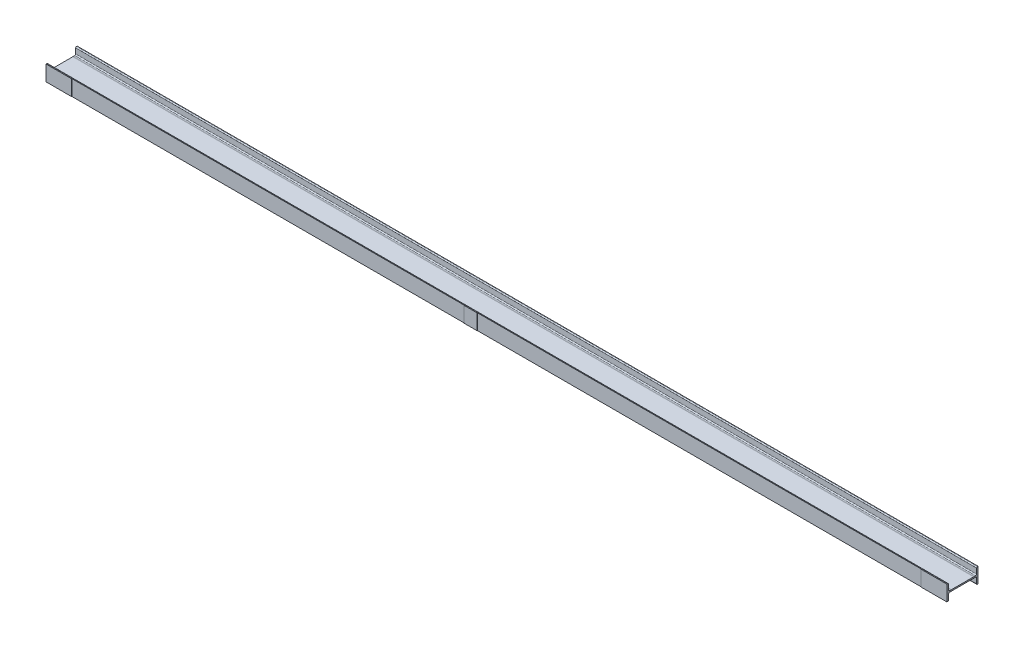
SolidWorks part; units mm, degrees
material "Hierro dúctil"
ref_plane "Alzado" through (0, 0, 0) normal (0, 0, 1) x (1, 0, 0)
ref_plane "Planta" through (0, 0, 0) normal (0, 1, 0) x (1, 0, 0)
ref_plane "Vista lateral" through (0, 0, 0) normal (1, 0, 0) x (0, 0, -1)
sketch "Croquis1" plane through (0, 0, 0) normal (0, 0, 1) x (1, 0, 0)
  line L0 (0, 0) -> (3500, 0)
  dimension "D1" = 3500
other "Viga sb 120 X 12(2)"
ref_plane "Plano1" through (0, 0, 0) normal (1, 0, 0) x (0, 1, 0)
sketch "Sketch12" plane through (0, 0, 0) normal (1, 0, 0) x (0, 1, 0)
  line L0 (-30, -60) -> (-30, -58.0801)
  line L1 (-26.6576, -54.1345) -> (-9.1847, -51.2221)
  line L2 (-2.5, -43.331) -> (-2.5, 43.331)
  line L3 (-9.1847, 51.2221) -> (-26.6576, 54.1345)
  line L4 (-30, 58.0801) -> (-30, 60)
  line L5 (-30, 60) -> (30, 60)
  line L6 (30, 60) -> (30, 58.0801)
  line L7 (26.6576, 54.1345) -> (9.1847, 51.2221)
  line L8 (2.5, 43.331) -> (2.5, -43.331)
  line L9 (9.1847, -51.2221) -> (26.6576, -54.1345)
  line L10 (30, -58.0801) -> (30, -60)
  line L11 (30, -60) -> (-30, -60)
  line L15 (-2.5, 0) -> (2.5, 0) construction
  arc A0 (-9.1847, -51.2221) -> (-2.5, -43.331) centre (-10.5, -43.331) ccw
  arc A1 (-2.5, 43.331) -> (-9.1847, 51.2221) centre (-10.5, 43.331) ccw
  arc A2 (9.1847, 51.2221) -> (2.5, 43.331) centre (10.5, 43.331) ccw
  arc A3 (2.5, -43.331) -> (9.1847, -51.2221) centre (10.5, -43.331) ccw
  arc A4 (-26.6576, 54.1345) -> (-30, 58.0801) centre (-26, 58.0801) cw
  arc A5 (26.6576, 54.1345) -> (30, 58.0801) centre (26, 58.0801) ccw
  arc A6 (-30, -58.0801) -> (-26.6576, -54.1345) centre (-26, -58.0801) cw
  arc A7 (30, -58.0801) -> (26.6576, -54.1345) centre (26, -58.0801) ccw
  point P1 (0, 60)
  point P8 (0, -60)
  point P21 (0, 0)
  point P34 (0, 0)
  dimension "RI" = 8
  dimension "D3" = 4
  dimension "BF" = 60
  dimension "D2" = 9.463
  dimension "DEPTH" = 120
  dimension "TW" = 5
  dimension "D1" = 86.662
sketch "Croquis3" plane through (0, 0, 0) normal (-1, 0, 0) x (0, 0, 1)
  line L0 (0, 0) -> (0, 20.5092) construction
  line L1 (54.1345, 26.6576) -> (44.9002, 26.6576)
  line L2 (54.1345, 26.6576) -> (54.1345, 6.6554)
  line L3 (50.1345, 2.6554) -> (44.9002, 2.6554)
  line L4 (44.9002, 26.6576) -> (44.9002, 2.6554)
  line L5 (54.1345, -26.6576) -> (43.331, -26.6576)
  line L6 (54.1345, -26.6576) -> (54.1345, -6.5)
  line L7 (50.1345, -2.5) -> (43.331, -2.5)
  line L8 (43.331, -26.6576) -> (43.331, -2.5)
  line L9 (-43.331, -26.6576) -> (-43.331, -2.5)
  line L10 (-50.1345, -2.5) -> (-43.331, -2.5)
  line L11 (-54.1345, -26.6576) -> (-54.1345, -6.5)
  line L12 (-54.1345, -26.6576) -> (-43.331, -26.6576)
  line L13 (-44.9002, 26.6576) -> (-44.9002, 2.6554)
  line L14 (-50.1345, 2.6554) -> (-44.9002, 2.6554)
  line L15 (-54.1345, 26.6576) -> (-54.1345, 6.6554)
  line L16 (-54.1345, 26.6576) -> (-44.9002, 26.6576)
  arc A1 (43.331, 2.5) -> (51.2221, 9.1847) centre (43.331, 10.5) ccw construction
  arc A2 (54.1345, -6.5) -> (50.1345, -2.5) centre (50.1345, -6.5) ccw
  arc A3 (50.1345, 2.6554) -> (54.1345, 6.6554) centre (50.1345, 6.6554) ccw
  arc A4 (-54.1345, -6.5) -> (-50.1345, -2.5) centre (-50.1345, -6.5) cw
  arc A5 (-50.1345, 2.6554) -> (-54.1345, 6.6554) centre (-50.1345, 6.6554) cw
  point P30 (54.1345, -2.5)
  point P33 (54.1345, 2.6554)
  point P36 (-54.1345, -2.5)
  point P39 (-54.1345, 2.6554)
  dimension "D5" = 4
  dimension "D1" = 24.0022
  dimension "D2" = 9.2343
  dimension "D3" = 24.1576
  dimension "D4" = 10.8035
extrude "Cortar-Extruir1" cut sketch "Croquis3" against normal through all both and the other way through all
sketch "Croquis4" plane through (0, 0, 60) normal (0, 0, 1) x (1, 0, 0)
  line L0 (3500, 30) -> (0, 30) construction
  line L1 (1624.8292, -30) -> (1675.1708, -30)
  line L2 (1624.8292, -30) -> (1624.8292, 30)
  line L3 (1624.8292, 30) -> (1675.1708, 30)
  line L4 (1675.1708, -30) -> (1675.1708, 30)
  line L5 (1624.8292, -30) -> (1675.1708, 30) construction
  line L6 (1624.8292, 30) -> (1675.1708, -30) construction
  point P0 (1650, 0)
  dimension "D1" = 60
  dimension "D2" = 50.3417
  dimension "D3" = 1650
extrude "Saliente-Extruir1" add sketch "Croquis4" along normal blind 1 separate body
sketch "Croquis6" plane through (0, 0, 60) normal (0, 0, 1) x (1, 0, 0)
  line L2 (3500, 30) -> (3400, 30)
  line L3 (3500, 30) -> (3500, -30)
  line L4 (3500, -30) -> (3400, -30)
  line L5 (3500, -30) -> (0, -30) construction
  line L7 (3400, 30) -> (3400, -30)
  line L8 (0, 30) -> (100, 30)
  line L9 (0, 30) -> (0, -30)
  line L10 (0, -30) -> (100, -30)
  line L12 (100, 30) -> (100, -30)
  dimension "D1" = 60
  dimension "D2" = 60
  dimension "D3" = 100
  dimension "D4" = 100
extrude "Saliente-Extruir2" add sketch "Croquis6" along normal blind 1 separate body
sketch "Croquis7" plane through (0, 0, 0) normal (-1, 0, 0) x (0, 0, 1)
  line L1 (54.1345, -6.6554) -> (-54.1345, -6.6554)
  line L2 (54.1345, -6.6554) -> (54.1345, 6.6554)
  line L3 (54.1345, 6.6554) -> (-54.1345, 6.6554)
  line L4 (-54.1345, -6.6554) -> (-54.1345, 6.6554)
  line L5 (54.1345, -6.6554) -> (-54.1345, 6.6554) construction
  line L6 (54.1345, 6.6554) -> (-54.1345, -6.6554) construction
  point P0 (0, 0)
  dimension "D1" = 13.3108
  dimension "D2" = 108.269
extrude "Saliente-Extruir3" [suppressed] add sketch "Croquis7" against normal blind 100
sketch "Croquis8" plane through (3500, 0, 0) normal (1, 0, 0) x (0, 0, -1)
  line L1 (-54.1345, 6.5) -> (54.1345, 6.5)
  line L2 (-54.1345, 6.5) -> (-54.1345, -6.5)
  line L3 (-54.1345, -6.5) -> (54.1345, -6.5)
  line L4 (54.1345, 6.5) -> (54.1345, -6.5)
  line L5 (-54.1345, 6.5) -> (54.1345, -6.5) construction
  line L6 (-54.1345, -6.5) -> (54.1345, 6.5) construction
  point P0 (0, 0)
  dimension "D1" = 13
  dimension "D2" = 108.269
extrude "Saliente-Extruir4" [suppressed] add sketch "Croquis8" against normal blind 100
